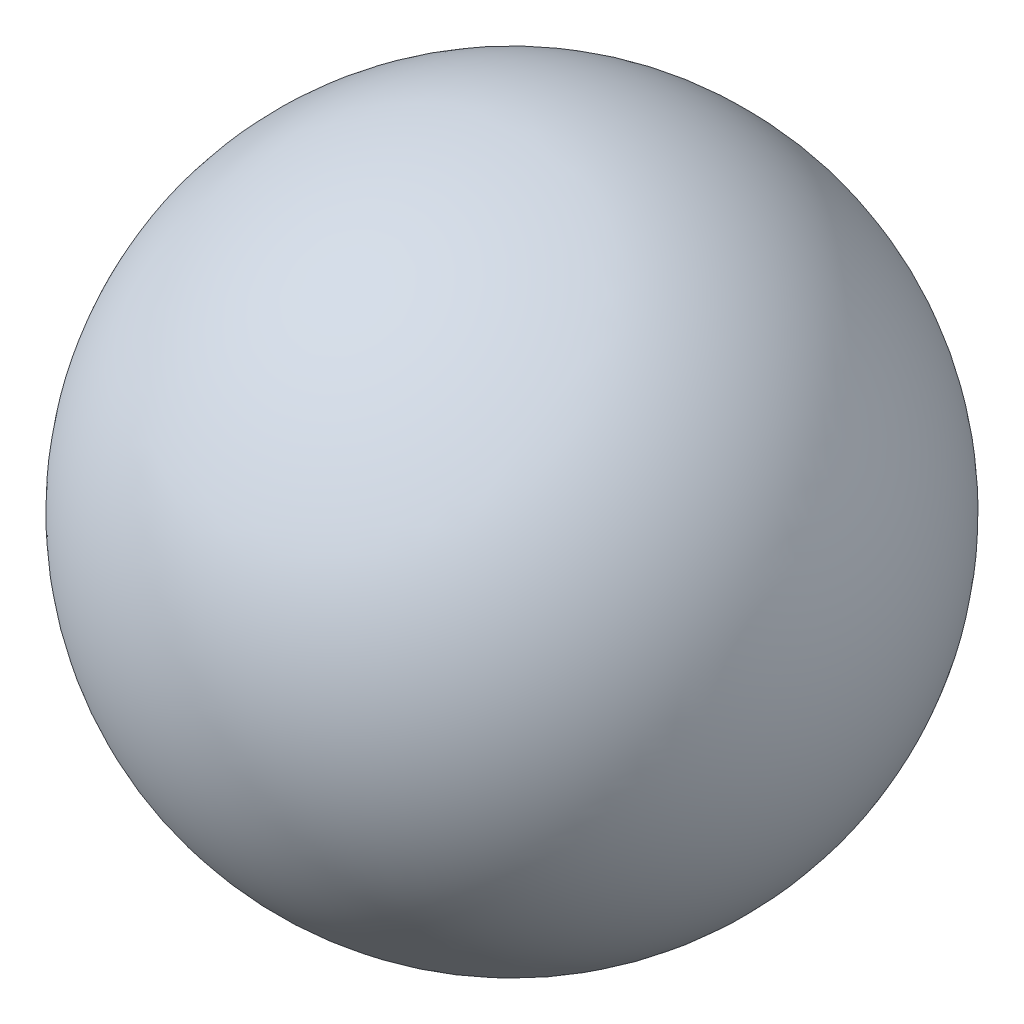
SolidWorks part; units mm, degrees
ref_plane "Front Plane" through (0, 0, 0) normal (0, 0, 1) x (1, 0, 0)
ref_plane "Top Plane" through (0, 0, 0) normal (0, 1, 0) x (1, 0, 0)
ref_plane "Right Plane" through (0, 0, 0) normal (1, 0, 0) x (0, 0, -1)
sketch "Sketch2" plane through (0, 0, 0) normal (0, 0, 1) x (1, 0, 0)
  line L0 (0, 0) -> (11, 0) construction
  line L1 (0, 0) -> (11, 0)
  arc A0 (0, 0) -> (11, 0) centre (5.5, 0) cw
  point P5 (5.5, 0)
  dimension "D1" = 11
revolve "Revolve1" add sketch "Sketch2" angle 360 about L0
